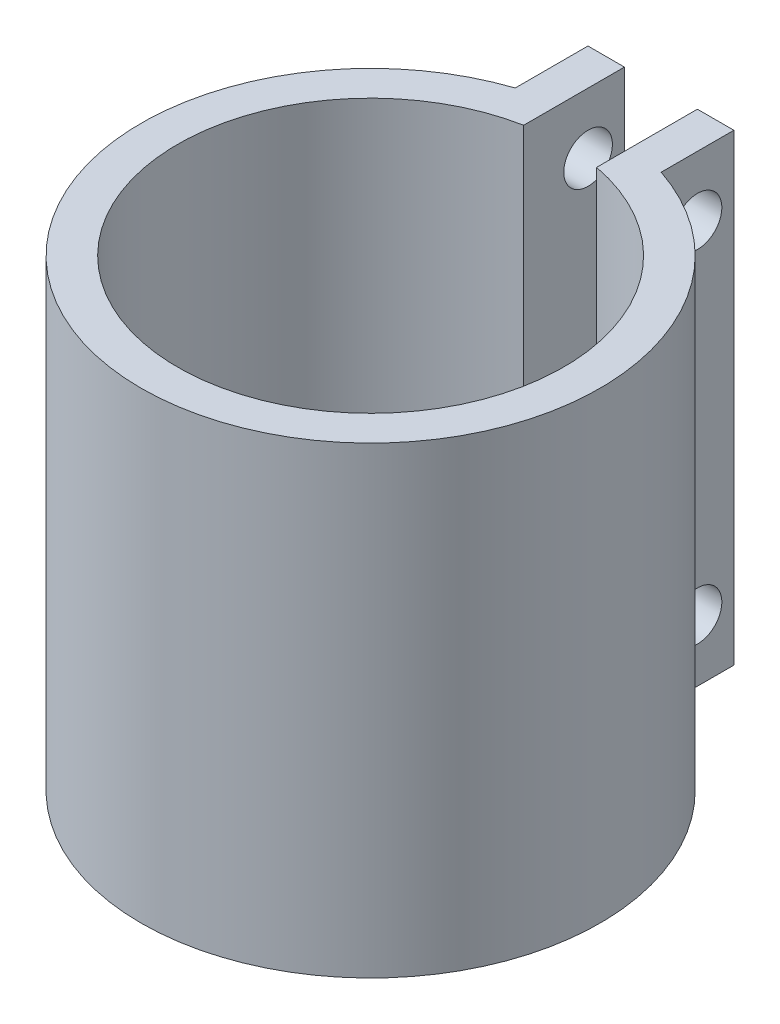
SolidWorks part; units mm, degrees
ref_plane "Front" through (0, 0, 0) normal (0, 0, 1) x (1, 0, 0)
ref_plane "Top" through (0, 0, 0) normal (0, 1, 0) x (1, 0, 0)
ref_plane "Right" through (0, 0, 0) normal (1, 0, 0) x (0, 0, -1)
sketch "Sketch1" plane through (0, 0, 0) normal (0, 1, 0) x (1, 0, 0)
  line L0 (0, 15.875) -> (0, 23.875) construction
  line L1 (3, 15.875) -> (3, 23.875)
  line L2 (-3, 15.875) -> (-3, 23.875)
  line L3 (6, 17.896) -> (6, 23.875)
  line L4 (6, 23.875) -> (3, 23.875)
  line L5 (-6, 17.896) -> (-6, 23.875)
  line L6 (-3, 23.875) -> (-6, 23.875)
  line L7 (3, 15.875) -> (3, 15.589)
  line L8 (-3, 15.875) -> (-3, 15.589)
  line L9 (-6, 15.875) -> (-6, 23.875) construction
  line L10 (6, 15.875) -> (6, 23.875) construction
  arc A0 (-3, 15.589) -> (3, 15.589) centre (0, 0) ccw
  arc A1 (-6, 17.896) -> (6, 17.896) centre (0, 0) ccw
  circle A2 centre (0, 0) radius 18.875 construction
  circle A4 centre (0, 0) radius 15.875 construction
  dimension "D1" = 31.75
  dimension "D3" = 8
  dimension "D2" = 3
  dimension "D4" = 3
  dimension "D5" = 3
  dimension "D6" = 3
  dimension "D7" = 3
extrude "Boss-Extrude1" add sketch "Sketch1" along normal blind 38.1
sketch "Sketch2" plane through (-6, 0, 0) normal (-1, 0, 0) x (0, 0, 1)
  line L0 (-20.8855, 38.1) -> (-20.8855, 0) construction
  line L1 (-23.875, 38.1) -> (-17.896, 38.1) construction
  line L2 (-23.875, 0) -> (-17.896, 0) construction
  circle A0 centre (-20.8855, 33.1) radius 2
  circle A1 centre (-20.8855, 5) radius 2
  dimension "D1" = 4
  dimension "D2" = 5
  dimension "D3" = 5
extrude "Cut-Extrude1" cut sketch "Sketch2" against normal through all
